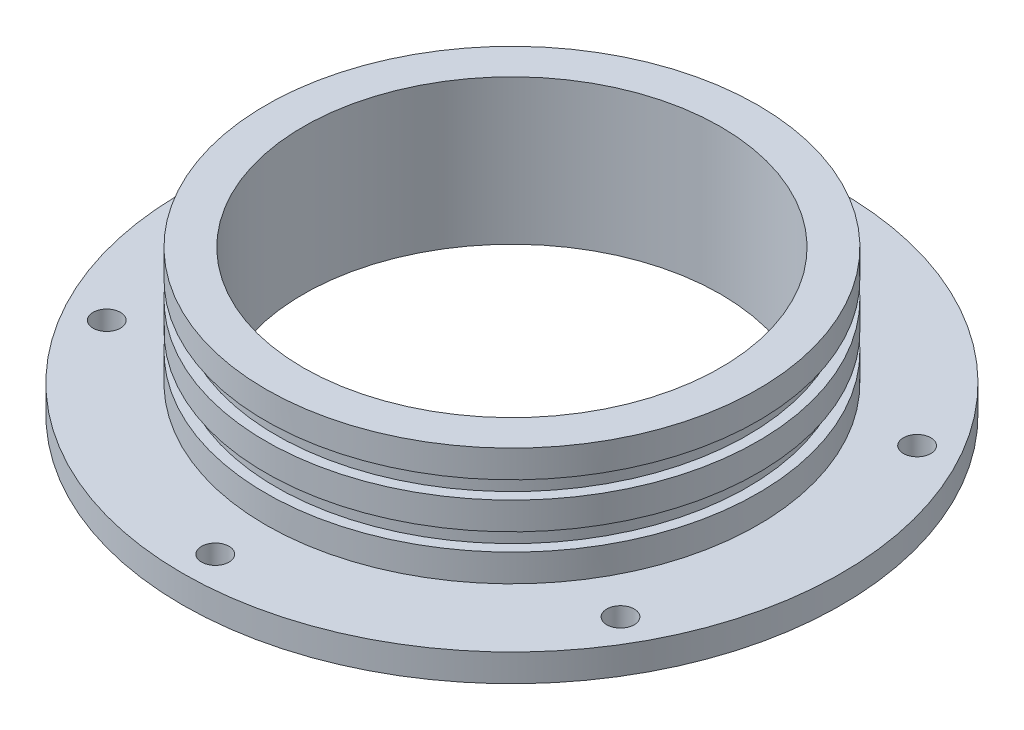
SolidWorks part; units mm, degrees
ref_plane "Front Plane" through (0, 0, 0) normal (0, 0, 1) x (1, 0, 0)
ref_plane "Top Plane" through (0, 0, 0) normal (0, 1, 0) x (1, 0, 0)
ref_plane "Right Plane" through (0, 0, 0) normal (1, 0, 0) x (0, 0, -1)
sketch "Sketch1" plane through (0, 0, 0) normal (0, 1, 0) x (1, 0, 0)
  circle A0 centre (0, 0) radius 60
  circle A1 centre (0, 0) radius 38
extrude "Boss-Extrude1" add sketch "Sketch1" along normal blind 5
sketch "Sketch2" plane through (0, 5, 0) normal (0, 1, 0) x (1, 0, 0)
  circle A0 centre (0, 0) radius 44.8
  circle A1 centre (0, 0) radius 60
  circle A2 centre (0, 0) radius 60
  circle M3 centre (0, 0) radius 38
  dimension "D1" = 0
extrude "Boss-Extrude2" add sketch "Sketch2" along normal blind 21.4 contours A0 M3
sketch "Sketch3" plane through (0, 0, 0) normal (1, 0, 0) x (0, 0, -1)
  line L0 (60, 5) -> (-60, 5) construction
  line L1 (60, 5) -> (-60, 5) construction
  line L2 (-44.8, 26.4) -> (-44.8, 5) construction
  line L3 (-44.8, 26.4) -> (-44.8, 5) construction
  line L4 (-44.8, 5) -> (-44.8, 10)
  line L5 (-44.8, 10) -> (-42.9, 10)
  line L6 (-42.9, 10) -> (-42.9, 13.2)
  line L7 (-42.9, 13.2) -> (-44.8, 13.2)
  line L8 (-44.8, 13.2) -> (-44.8, 18.2)
  line L9 (-44.8, 18.2) -> (-42.9, 18.2)
  line L10 (-42.9, 18.2) -> (-42.9, 21.4)
  line L11 (-42.9, 21.4) -> (-44.8, 21.4)
  line L12 (-44.8, 21.4) -> (-44.8, 26.4)
  line L13 (-44.8, 21.4) -> (-45.9729, 21.4)
  line L14 (-45.9729, 21.4) -> (-45.9729, 18.2)
  line L15 (0, 0) -> (0, 31.0021) construction
  line L16 (-44.8, 10) -> (-45.9729, 10)
  line L17 (-45.9729, 10) -> (-45.9729, 18.2)
  line L18 (-44.8, 18.2) -> (-44.8, 13.2)
revolve "Cut-Revolve1" cut sketch "Sketch3" angle 360 about L15
sketch "Sketch4" plane through (0, 0, 0) normal (0, -1, 0) x (1, 0, 0)
  line L0 (0, 0) -> (0, 54) construction
  circle A0 centre (0, 54) radius 2.5
  circle A1 centre (0, 0) radius 60
  circle A2 centre (0, 0) radius 60
  circle A3 centre (46.7654, 27) radius 2.5
  circle A4 centre (46.7654, -27) radius 2.5
  circle A5 centre (0, -54) radius 2.5
  circle A6 centre (-46.7654, -27) radius 2.5
  circle A7 centre (-46.7654, 27) radius 2.5
  point P18 (0, 0)
  dimension "D2" = 6
  dimension "D1" = 0
extrude "Cut-Extrude1" cut sketch "Sketch4" against normal blind 20
